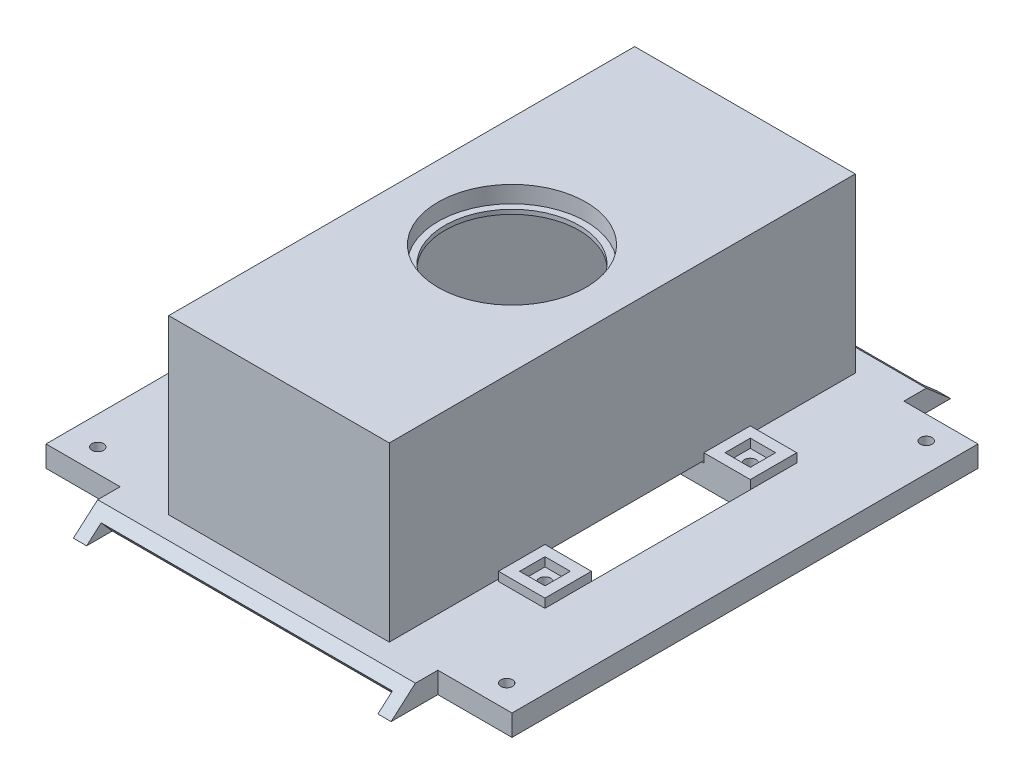
SolidWorks part; units mm, degrees
ref_plane "Front Plane" through (0, 0, 0) normal (0, 0, 1) x (1, 0, 0)
ref_plane "Top Plane" through (0, 0, 0) normal (0, 1, 0) x (1, 0, 0)
ref_plane "Right Plane" through (0, 0, 0) normal (1, 0, 0) x (0, 0, -1)
sketch "Sketch1" plane through (0, 0, 0) normal (0, 1, 0) x (1, 0, 0)
  line L1 (44, -44) -> (-44, -44)
  line L2 (44, -44) -> (44, 44)
  line L3 (44, 44) -> (-44, 44)
  line L4 (-44, -44) -> (-44, 44)
  line L5 (44, -44) -> (-44, 44) construction
  line L6 (44, 44) -> (-44, -44) construction
  point P0 (0, 0)
  dimension "D1" = 88
extrude "Boss-Extrude1" add sketch "Sketch1" along normal blind 4
sketch "Sketch2" plane through (0, 4, 0) normal (0, 1, 0) x (1, 0, 0)
  line L0 (44, 44) -> (-44, 44) construction
  line L1 (20.8275, -44) -> (-20.8275, -44)
  line L2 (20.8275, -44) -> (20.8275, 44)
  line L3 (20.8275, 44) -> (-20.8275, 44)
  line L4 (-20.8275, -44) -> (-20.8275, 44)
  line L5 (20.8275, -44) -> (-20.8275, 44) construction
  line L6 (20.8275, 44) -> (-20.8275, -44) construction
  line L8 (16.8275, -41.275) -> (-16.8275, -41.275)
  line L9 (16.8275, -41.275) -> (16.8275, 41.275)
  line L10 (16.8275, 41.275) -> (-16.8275, 41.275)
  line L11 (-16.8275, -41.275) -> (-16.8275, 41.275)
  line L12 (16.8275, -41.275) -> (-16.8275, 41.275) construction
  line L13 (16.8275, 41.275) -> (-16.8275, -41.275) construction
  point P0 (0, 0)
  point P8 (0, 0)
  dimension "D1" = 4
  dimension "D2" = 82.55
  dimension "D3" = 33.655
extrude "Boss-Extrude2" add sketch "Sketch2" along normal blind 28.575
sketch "Sketch4" plane through (0, 4, 0) normal (0, 1, 0) x (1, 0, 0)
  line L4 (16.8275, 41.275) -> (-16.8275, 41.275)
  line L5 (-16.8275, 41.275) -> (-16.8275, -41.275)
  line L6 (-16.8275, -41.275) -> (16.8275, -41.275)
  line L7 (16.8275, -41.275) -> (16.8275, 41.275)
  line L8 (16.8275, 41.275) -> (-16.8275, 41.275)
  line L9 (-16.8275, 41.275) -> (-16.8275, -41.275)
  line L10 (-16.8275, -41.275) -> (16.8275, -41.275)
  line L11 (16.8275, -41.275) -> (16.8275, 41.275)
  dimension "D1" = 0
extrude "Cut-Extrude1" cut sketch "Sketch4" against normal through all
sketch "Sketch5" plane through (0, 32.575, 0) normal (0, 1, 0) x (1, 0, 0)
  line L4 (-20.8275, 44) -> (-20.8275, -44)
  line L5 (-20.8275, -44) -> (20.8275, -44)
  line L6 (20.8275, -44) -> (20.8275, 44)
  line L7 (20.8275, 44) -> (-20.8275, 44)
  line L8 (-20.8275, 44) -> (-20.8275, -44)
  line L9 (-20.8275, -44) -> (20.8275, -44)
  line L10 (20.8275, -44) -> (20.8275, 44)
  line L11 (20.8275, 44) -> (-20.8275, 44)
  dimension "D1" = 0
extrude "Boss-Extrude3" add sketch "Sketch5" along normal blind 4
sketch "Sketch6" plane through (0, 36.575, 0) normal (0, 1, 0) x (1, 0, 0)
  circle A0 centre (0, 0) radius 13.97
  dimension "D1" = 27.94
extrude "Cut-Extrude2" cut sketch "Sketch6" against normal blind 3.175
sketch "Sketch7" plane through (0, 33.4, 0) normal (0, 1, 0) x (1, 0, 0)
  circle A0 centre (0, 0) radius 12.7
  dimension "D1" = 25.4
extrude "Cut-Extrude3" cut sketch "Sketch7" against normal through all
sketch "Sketch8" plane through (0, 0, 0) normal (0, -1, 0) x (1, 0, 0)
  line L1 (30, -15) -> (-30, -15)
  line L2 (30, -15) -> (30, 15)
  line L3 (30, 15) -> (-30, 15)
  line L4 (-30, -15) -> (-30, 15)
  line L5 (30, -15) -> (-30, 15) construction
  line L6 (30, 15) -> (-30, -15) construction
  point P0 (0, 0)
  dimension "D1" = 60
  dimension "D2" = 30
extrude "Cut-Extrude4" cut sketch "Sketch8" against normal blind 4
sketch "Sketch9" plane through (0, 0, 0) normal (0, -1, 0) x (1, 0, 0)
  line L0 (-16.8275, 15) -> (-20.8275, 15) construction
  line L1 (-30, 23.7752) -> (-21.2248, 23.7752)
  line L2 (-30, 23.7752) -> (-30, 15)
  line L3 (-30, 15) -> (-21.2248, 15)
  line L4 (-21.2248, 23.7752) -> (-21.2248, 15)
  line L5 (-30, 23.7752) -> (-21.2248, 15) construction
  line L6 (-30, 15) -> (-21.2248, 23.7752) construction
  line L7 (0, 0) -> (-30, 0) construction
  line L8 (-23.2248, 17) -> (-28, 17)
  line L9 (-23.2248, 17) -> (-23.2248, 21.7752)
  line L10 (-23.2248, 21.7752) -> (-28, 21.7752)
  line L11 (-28, 17) -> (-28, 21.7752)
  line L12 (-23.2248, 17) -> (-28, 21.7752) construction
  line L13 (-23.2248, 21.7752) -> (-28, 17) construction
  line L14 (-30, 15) -> (-30, -15) construction
  line L15 (0, 0) -> (0, 41.275) construction
  line L16 (-16.8275, 41.275) -> (16.8275, 41.275) construction
  line L17 (23.2248, 21.7752) -> (28, 17) construction
  line L18 (23.2248, 17) -> (28, 21.7752) construction
  line L19 (30, 15) -> (21.2248, 23.7752) construction
  line L20 (30, 23.7752) -> (21.2248, 15) construction
  line L21 (28, 17) -> (28, 21.7752)
  line L22 (23.2248, 21.7752) -> (28, 21.7752)
  line L23 (23.2248, 17) -> (23.2248, 21.7752)
  line L24 (23.2248, 17) -> (28, 17)
  line L25 (21.2248, 23.7752) -> (21.2248, 15)
  line L26 (30, 15) -> (21.2248, 15)
  line L27 (30, 23.7752) -> (30, 15)
  line L28 (30, 23.7752) -> (21.2248, 23.7752)
  line L29 (30, -23.7752) -> (21.2248, -15) construction
  line L30 (30, -15) -> (21.2248, -23.7752) construction
  line L31 (23.2248, -17) -> (28, -21.7752) construction
  line L32 (23.2248, -21.7752) -> (28, -17) construction
  line L33 (-23.2248, -21.7752) -> (-28, -17) construction
  line L34 (-23.2248, -17) -> (-28, -21.7752) construction
  line L35 (-30, -15) -> (-21.2248, -23.7752) construction
  line L36 (-30, -23.7752) -> (-21.2248, -15) construction
  line L37 (30, -23.7752) -> (21.2248, -23.7752)
  line L38 (30, -23.7752) -> (30, -15)
  line L39 (30, -15) -> (21.2248, -15)
  line L40 (21.2248, -23.7752) -> (21.2248, -15)
  line L41 (23.2248, -17) -> (28, -17)
  line L42 (23.2248, -17) -> (23.2248, -21.7752)
  line L43 (23.2248, -21.7752) -> (28, -21.7752)
  line L44 (28, -17) -> (28, -21.7752)
  line L45 (-28, -17) -> (-28, -21.7752)
  line L46 (-23.2248, -21.7752) -> (-28, -21.7752)
  line L47 (-23.2248, -17) -> (-23.2248, -21.7752)
  line L48 (-23.2248, -17) -> (-28, -17)
  line L49 (-21.2248, -23.7752) -> (-21.2248, -15)
  line L50 (-30, -15) -> (-21.2248, -15)
  line L51 (-30, -23.7752) -> (-30, -15)
  line L52 (-30, -23.7752) -> (-21.2248, -23.7752)
  point P0 (-25.6124, 19.3876)
  point P7 (-25.6124, 19.3876)
  point P29 (25.6124, 19.3876)
  point P46 (25.6124, -19.3876)
  point P47 (-25.6124, -19.3876)
  dimension "D1" = 4.7752
  dimension "D2" = 2
extrude "Boss-Extrude4" add sketch "Sketch9" against normal blind 5.6764
sketch "Sketch10" plane through (0, 0, 0) normal (0, -1, 0) x (1, 0, 0)
  line L0 (-25.6124, 21.7752) -> (-25.6124, 17) construction
  line L1 (-23.2248, 21.7752) -> (-28, 21.7752) construction
  line L2 (-28, 17) -> (-23.2248, 17) construction
  line L3 (-30, 0) -> (0, 0) construction
  line L4 (-30, 15) -> (-30, -15) construction
  line L5 (0, 0) -> (0, 41.275) construction
  line L6 (-16.8275, 41.275) -> (16.8275, 41.275) construction
  circle A0 centre (-25.6124, 19.3876) radius 1.1
  circle A1 centre (25.6124, 19.3876) radius 1.1
  circle A2 centre (25.6124, -19.3876) radius 1.1
  circle A3 centre (-25.6124, -19.3876) radius 1.1
  dimension "D1" = 2.2
extrude "Cut-Extrude5" cut sketch "Sketch10" against normal through all
sketch "Sketch11" plane through (0, 4, 0) normal (0, 1, 0) x (1, 0, 0)
  line L0 (-44, 44) -> (-44, -44) construction
  line L1 (-20.8275, 44) -> (-44, 44) construction
  line L2 (0, 44) -> (0, 0) construction
  line L3 (20.8275, 44) -> (-20.8275, 44) construction
  line L4 (0, 0) -> (-44, 0) construction
  circle A0 centre (-38.6124, 39.6124) radius 1.1
  circle A1 centre (38.6124, 39.6124) radius 1.1
  circle A2 centre (38.6124, -39.6124) radius 1.1
  circle A3 centre (-38.6124, -39.6124) radius 1.1
  dimension "D3" = 2.2
  dimension "D1" = 5.3876
  dimension "D2" = 4.3876
extrude "Cut-Extrude6" cut sketch "Sketch11" against normal through all
sketch "Sketch14" plane through (0, 0, 0) normal (1, 0, 0) x (0, 0, -1)
  line L0 (-44, 4) -> (-48.2382, 4)
  line L1 (-48.2382, 4) -> (-52.8285, 0)
  line L2 (-52.8285, 0) -> (-44, 0)
  line L3 (-44, 0) -> (-44, 4)
  line L4 (-44, 0) -> (-72.575, -24.9) construction
  line L5 (-72.575, -24.9) -> (-44, -24.9) construction
  line L6 (-44, -24.9) -> (-44, 0) construction
  line L7 (-52.8285, 0) -> (-60.3677, -6.5696) construction
  line L8 (-60.3677, -6.5696) -> (-56.5574, -10.9424) construction
  line L9 (0, 0) -> (0, 36.575) construction
  line L10 (-44, 36.575) -> (44, 36.575) construction
  line L11 (44, 0) -> (44, 4)
  line L12 (52.8285, 0) -> (44, 0)
  line L13 (48.2382, 4) -> (52.8285, 0)
  line L14 (44, 4) -> (48.2382, 4)
  dimension "D1" = 24.9
  dimension "D2" = 28.575
  dimension "D3" = 10
  dimension "D4" = 5.8
extrude "Boss-Extrude5" add sketch "Sketch14" along normal mid plane 60
sketch "Sketch15" plane through (0, 0, 0) normal (1, 0, 0) x (0, 0, -1)
  line L0 (-50.0815, 2.3937) -> (-47.9957, 0)
  line L1 (-48.2382, 4) -> (-52.8285, 0) construction
  line L2 (-52.8285, 0) -> (-44, 0) construction
  line L3 (-47.9957, 0) -> (-50.7427, -2.3937)
  line L4 (-50.7427, -2.3937) -> (-52.8285, 0)
  line L5 (-52.8285, 0) -> (-50.0815, 2.3937)
  line L6 (0, 0) -> (0, 36.575) construction
  line L7 (-44, 0) -> (44, 0) construction
  line L8 (-44, 36.575) -> (44, 36.575) construction
  line L9 (52.8285, 0) -> (50.0815, 2.3937)
  line L10 (50.7427, -2.3937) -> (52.8285, 0)
  line L11 (47.9957, 0) -> (50.7427, -2.3937)
  line L12 (50.0815, 2.3937) -> (47.9957, 0)
  dimension "D1" = 3.175
extrude "Cut-Extrude7" cut sketch "Sketch15" against normal mid plane 55
